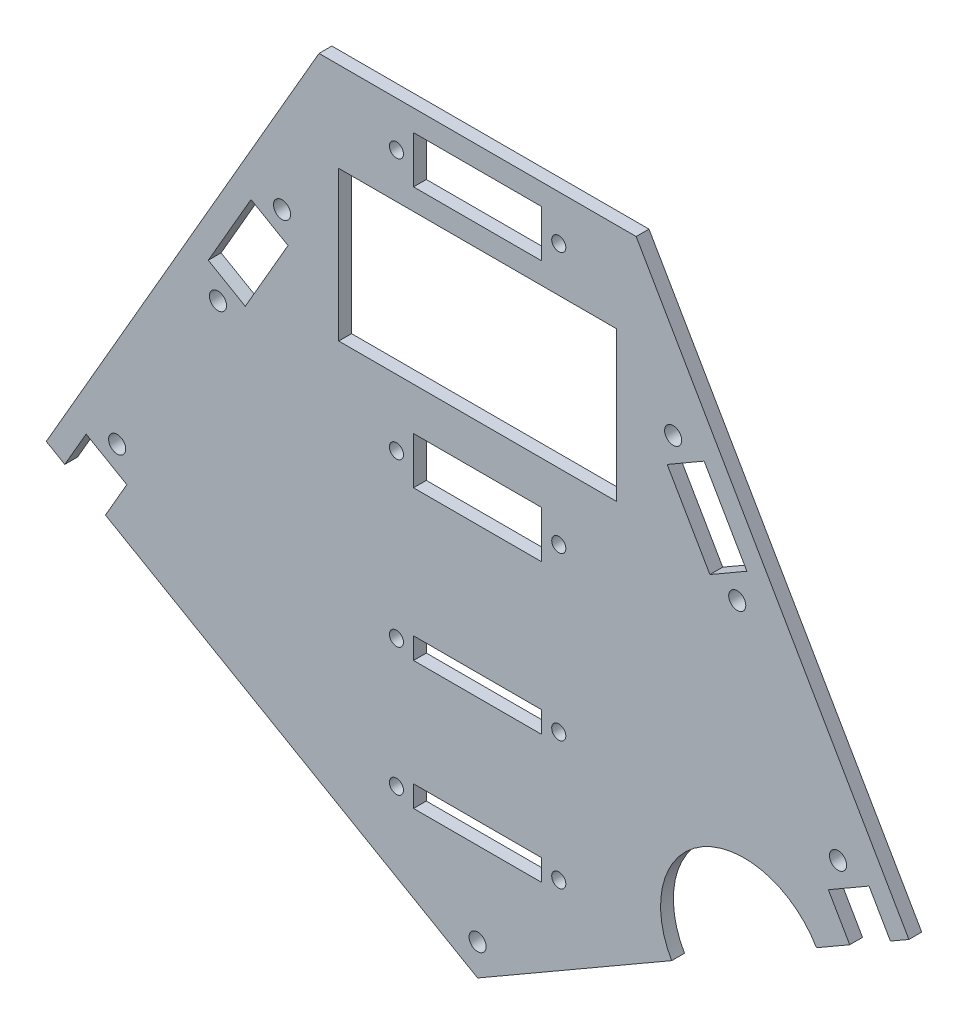
SolidWorks part; units mm, degrees
ref_plane "Plan de face" through (0, 0, 0) normal (0, 0, 1) x (1, 0, 0)
ref_plane "Plan de dessus" through (0, 0, 0) normal (0, 1, 0) x (1, 0, 0)
ref_plane "Plan de droite" through (0, 0, 0) normal (1, 0, 0) x (0, 0, -1)
sketch "Esquisse1" plane through (0, 0, 0) normal (0, 0, 1) x (1, 0, 0)
  line L0 (-32.5, 112.872) -> (32.5, 112.872)
  line L1 (32.5, 112.872) -> (114, -28.2902) construction
  line L2 (-82.6708, 68.9736) -> (-97.7336, 42.884) construction
  line L3 (81.5, -84.5818) -> (-81.5, -84.5818) construction
  line L4 (76.4496, 79.7491) -> (96.9986, 44.1572) construction
  line L5 (-114, -28.2902) -> (-32.5, 112.872) construction
  line L6 (-15, 61.872) -> (15, 61.872)
  line L7 (0, 84.8951) -> (0, 0) construction
  line L8 (15, 61.872) -> (15, 56.872)
  line L9 (108.528, -62.6587) -> (-0.0727, 0.042) construction
  line L10 (0, 0) -> (-107.4388, -62.0298) construction
  line L11 (15, 56.872) -> (-15, 56.872)
  line L12 (-15, 56.872) -> (-15, 61.872)
  line L13 (26.3257, 59.372) -> (-26.3257, 59.372) construction
  line L14 (15, 31.872) -> (15, 26.872)
  line L15 (15, 26.872) -> (-15, 26.872)
  line L16 (-15, 31.872) -> (15, 31.872)
  line L17 (-15, 102.872) -> (15, 102.872)
  line L18 (15, 102.872) -> (15, 91.872)
  line L19 (15, 91.872) -> (-15, 91.872)
  line L20 (-15, 91.872) -> (-15, 102.872)
  line L21 (-15, 26.872) -> (-15, 31.872)
  line L22 (-32.5, 112.872) -> (-32.5, 147.872)
  line L23 (-24.2975, 29.372) -> (23.7598, 29.372) construction
  line L24 (-139.9808, -43.2902) -> (-32.5, 142.872) construction
  line L25 (32.5, 142.872) -> (139.9808, -43.2902) construction
  line L26 (-32.5, 147.872) -> (32.5, 147.872)
  line L27 (32.5, 147.872) -> (32.5, 112.872)
  line L28 (-53.0391, 131.2973) -> (-63.0391, 113.9767)
  line L29 (-81.5, -84.5818) -> (-44.8099, -84.5818) construction
  line L30 (-53.0391, 131.2973) -> (-44.3788, 126.2973)
  line L31 (-63.0391, 113.9767) -> (-54.3788, 108.9767)
  line L32 (44.8099, -84.5818) -> (81.5, -84.5818) construction
  line L33 (-44.3788, 126.2973) -> (-54.3788, 108.9767)
  line L34 (63.0391, 113.9767) -> (54.3788, 108.9767)
  line L35 (-207.1218, -119.5818) -> (207.1218, -119.5818) construction
  line L36 (37.1188, 168.872) -> (100.9628, 58.2909)
  line L37 (-96.6327, 55.7909) -> (-100.9628, 58.2909)
  line L38 (-37.1188, 168.872) -> (37.1188, 168.872)
  line L39 (-37.1188, 168.872) -> (-100.9628, 58.2909)
  line L40 (100.9628, 58.2909) -> (96.6327, 55.7909)
  line L41 (96.6327, 55.7909) -> (91.6327, 64.4512)
  line L42 (87.1064, 50.2909) -> (82.1064, 58.9512)
  line L43 (44.3788, 126.2973) -> (54.3788, 108.9767)
  line L44 (-49.8692, 127.872) -> (56.9381, 127.872) construction
  line L45 (15, 102.872) -> (-15, 102.872)
  line L46 (-15, 91.872) -> (15, 91.872)
  line L47 (26.3257, 158.372) -> (-26.3257, 158.372) construction
  line L48 (0, 170.3911) -> (0, 255.2862) construction
  line L49 (-15, 163.872) -> (15, 163.872)
  line L50 (15, 152.872) -> (-15, 152.872)
  line L51 (-15, 163.872) -> (-15, 152.872)
  line L52 (15, 163.872) -> (-15, 163.872)
  line L53 (15, 152.872) -> (15, 163.872)
  line L54 (-15, 152.872) -> (15, 152.872)
  line L55 (91.6327, 64.4512) -> (82.1064, 58.9512)
  line L56 (87.1064, 50.2909) -> (0, 0)
  line L57 (26.3257, 97.372) -> (-26.3257, 97.372) construction
  line L58 (-96.6327, 55.7909) -> (-91.6327, 64.4512)
  line L59 (-87.1064, 50.2909) -> (-82.1064, 58.9512)
  line L60 (62.2558, -82.9138) -> (101.7182, -14.5628) construction
  line L61 (53.0391, 131.2973) -> (63.0391, 113.9767)
  line L62 (-91.6327, 64.4512) -> (-82.1064, 58.9512)
  line L63 (53.0391, 131.2973) -> (44.3788, 126.2973)
  line L64 (-139.9808, -43.2902) -> (-32.5, 142.872) construction
  line L67 (32.5, 142.872) -> (139.9808, -43.2902) construction
  line L70 (-107.4808, -99.5818) -> (107.4808, -99.5818) construction
  line L72 (-87.1064, 50.2909) -> (0, 0)
  circle A0 centre (-84.3695, 66.0313) radius 2
  circle A1 centre (84.3695, 66.0313) radius 2
  circle A2 centre (-19, 97.372) radius 1.65
  circle A3 centre (19, 97.372) radius 1.65
  circle A4 centre (19, 158.372) radius 1.65
  circle A5 centre (-19, 158.372) radius 1.65
  circle A6 centre (-19, 59.372) radius 1.65
  circle A7 centre (0, 7.3429) radius 2
  circle A8 centre (19, 59.372) radius 1.65
  circle A9 centre (19, 29.372) radius 1.65
  circle A10 centre (-19, 29.372) radius 1.65
  circle A11 centre (-45.7759, 132.8774) radius 2
  circle A12 centre (-60.7759, 106.8966) radius 2
  circle A13 centre (60.7759, 106.8966) radius 2
  circle A14 centre (45.7759, 132.8774) radius 2
  point P12 (-86.8695, 61.7012)
  point P15 (86.8695, 61.7012)
  point P93 (-15, 29.372)
  dimension "D18" = 30
  dimension "D33" = 38
  dimension "D19" = 5
  dimension "D6" = 15
  dimension "D7" = 15
  dimension "D30" = 5
  dimension "D2" = 120
  dimension "D4" = 35
  dimension "D5" = 197.4538
  dimension "D8" = 11
  dimension "D9" = 4
  dimension "D10" = 10
  dimension "D11" = 4
  dimension "D12" = 5
  dimension "D13" = 65
  dimension "D14" = 1
  dimension "D15" = 30
  dimension "D16" = 11
  dimension "D17" = 1
  dimension "D20" = 5
  dimension "D21" = 5
  dimension "D22" = 5
  dimension "D23" = 10
  dimension "D24" = 10
  dimension "D25" = 30
  dimension "D26" = 11
  dimension "D27" = 20
  dimension "D28" = 5
  dimension "D29" = 10
  dimension "D31" = 5
extrude "Boss.-Extru.1" add sketch "Esquisse1" along normal blind 3
sketch "Esquisse2" plane through (0, 0, 0) normal (0, 0, -1) x (-1, 0, 0)
  line L0 (-87.1064, 50.2909) -> (0, 0) construction
  line L1 (-45.4276, 26.2277) -> (-79.3214, 45.7962)
  arc A0 (-79.3214, 45.7962) -> (-45.4276, 26.2277) centre (-62.3971, 35.9728) cw
extrude "Enlèv. mat.-Extru.1" cut sketch "Esquisse2" against normal blind 10
